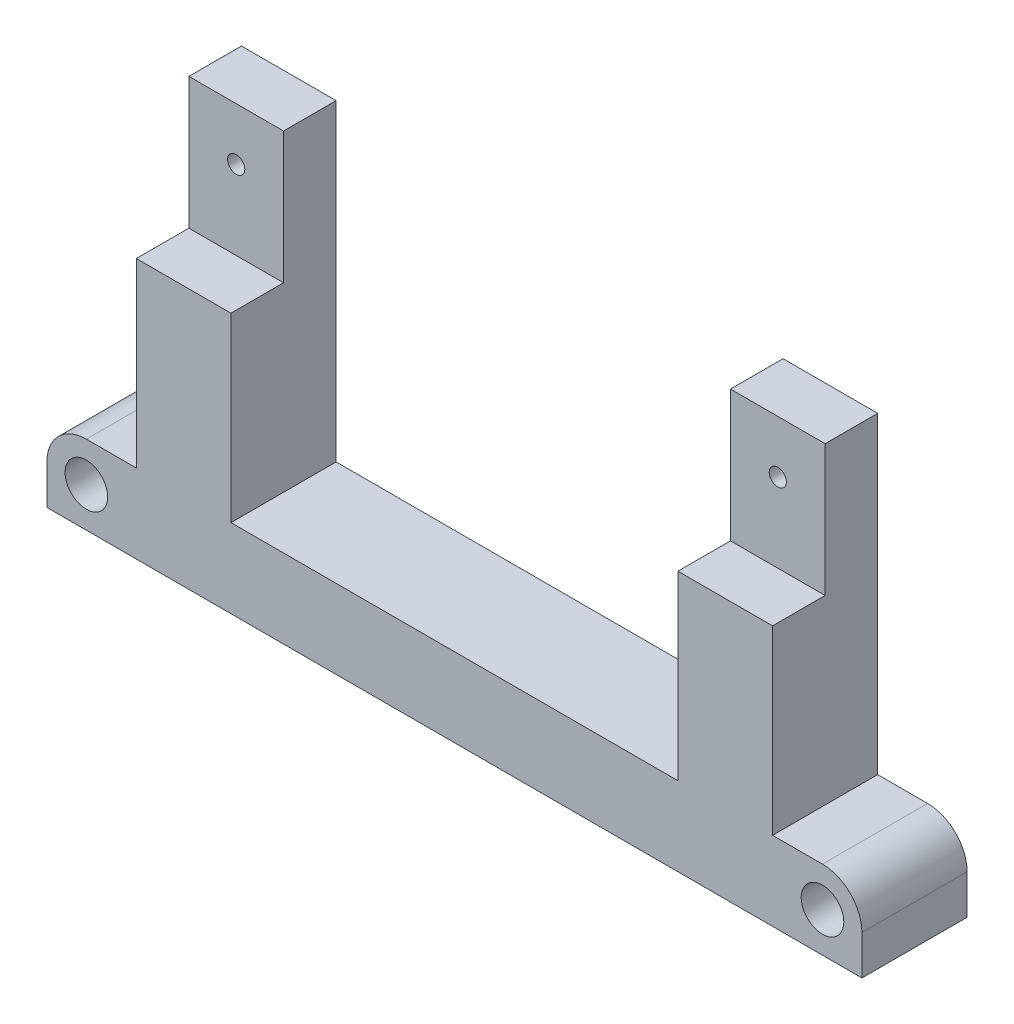
SolidWorks part; units mm, degrees
material "ABS"
ref_plane "Front Plane" through (0, 0, 0) normal (0, 0, 1) x (1, 0, 0)
ref_plane "Top Plane" through (0, 0, 0) normal (0, 1, 0) x (1, 0, 0)
ref_plane "Right Plane" through (0, 0, 0) normal (1, 0, 0) x (0, 0, -1)
sketch "Sketch1" plane through (0, 0, 0) normal (0, 0, 1) x (1, 0, 0)
  line L0 (-77.5, 0) -> (77.5, 0)
  line L1 (-70, 7.5) -> (70, 7.5) construction
  line L2 (-77.5, 0) -> (-77.5, 7.5)
  line L3 (-70, 15) -> (-60.5, 15)
  line L7 (60.5, 15) -> (70, 15)
  line L8 (77.5, 7.5) -> (77.5, 0)
  line L9 (-60.5, 15) -> (-60.5, 49.5)
  line L10 (-60.5, 49.5) -> (-42.5, 49.5)
  line L11 (-42.5, 49.5) -> (-42.5, 15)
  line L12 (-42.5, 15) -> (42.5, 15)
  line L13 (42.5, 15) -> (42.5, 49.5)
  line L14 (42.5, 49.5) -> (60.5, 49.5)
  line L15 (60.5, 49.5) -> (60.5, 15)
  circle A0 centre (-70, 7.5) radius 4.05
  circle A1 centre (70, 7.5) radius 4.05
  arc A2 (-77.5, 7.5) -> (-70, 15) centre (-70, 7.5) cw
  arc A3 (70, 15) -> (77.5, 7.5) centre (70, 7.5) cw
  point P2 (0, 0)
  point P8 (0, 7.5)
  dimension "D2" = 8.1
  dimension "D1" = 140
  dimension "D3" = 155
  dimension "D4" = 7.5
  dimension "D5" = 49.5
  dimension "D6" = 121
  dimension "D7" = 18
extrude "Boss-Extrude1" add sketch "Sketch1" along normal mid plane 20
sketch "Sketch2" plane through (0, 49.5, 0) normal (0, 1, 0) x (1, 0, 0)
  line L0 (60.5, -10) -> (60.5, 10) construction
  line L1 (42.5, 10) -> (60.5, 10)
  line L2 (42.5, 10) -> (42.5, 0)
  line L3 (42.5, 0) -> (60.5, 0)
  line L4 (60.5, 10) -> (60.5, 0)
  line L5 (-42.5, -10) -> (-42.5, 10) construction
  line L6 (-60.5, 10) -> (-42.5, 10)
  line L7 (-60.5, 10) -> (-60.5, 0)
  line L8 (-60.5, 0) -> (-42.5, 0)
  line L9 (-42.5, 10) -> (-42.5, 0)
extrude "Boss-Extrude2" add sketch "Sketch2" along normal blind 25
hole_wizard "#4 Clearance Hole1" positions "Sketch3" profile "Sketch4" hole size "#4" standard "ANSI Inch" end condition through all
sketch "Sketch3" plane through (0, 0, 0) normal (0, 0, 1) x (1, 0, 0)
  line L0 (-51.5, 64.5) -> (-51.5, 74.5) construction
  line L1 (-60.5, 74.5) -> (-42.5, 74.5) construction
  line L2 (51.5, 64.5) -> (51.5, 74.5) construction
  line L3 (42.5, 74.5) -> (60.5, 74.5) construction
  point P0 (-51.5, 64.5)
  point P2 (51.5, 64.5)
  dimension "D1" = 10
sketch "Sketch4" plane through (-51.5, 64.5, 0) normal (1, 0, 0) x (0, -1, 0)
  line L0 (0, 0) -> (0, 10)
  line L1 (0, 10) -> (1.6319, 10)
  line L2 (1.6319, 10) -> (1.6319, 0)
  line L5 (1.6319, 0) -> (0, 0)
  line L11 (0, -6.35) -> (0, 107.95) construction
  dimension "Thru Hole Dia." = 3.2639
  dimension "Thru Hole Depth" = 10
